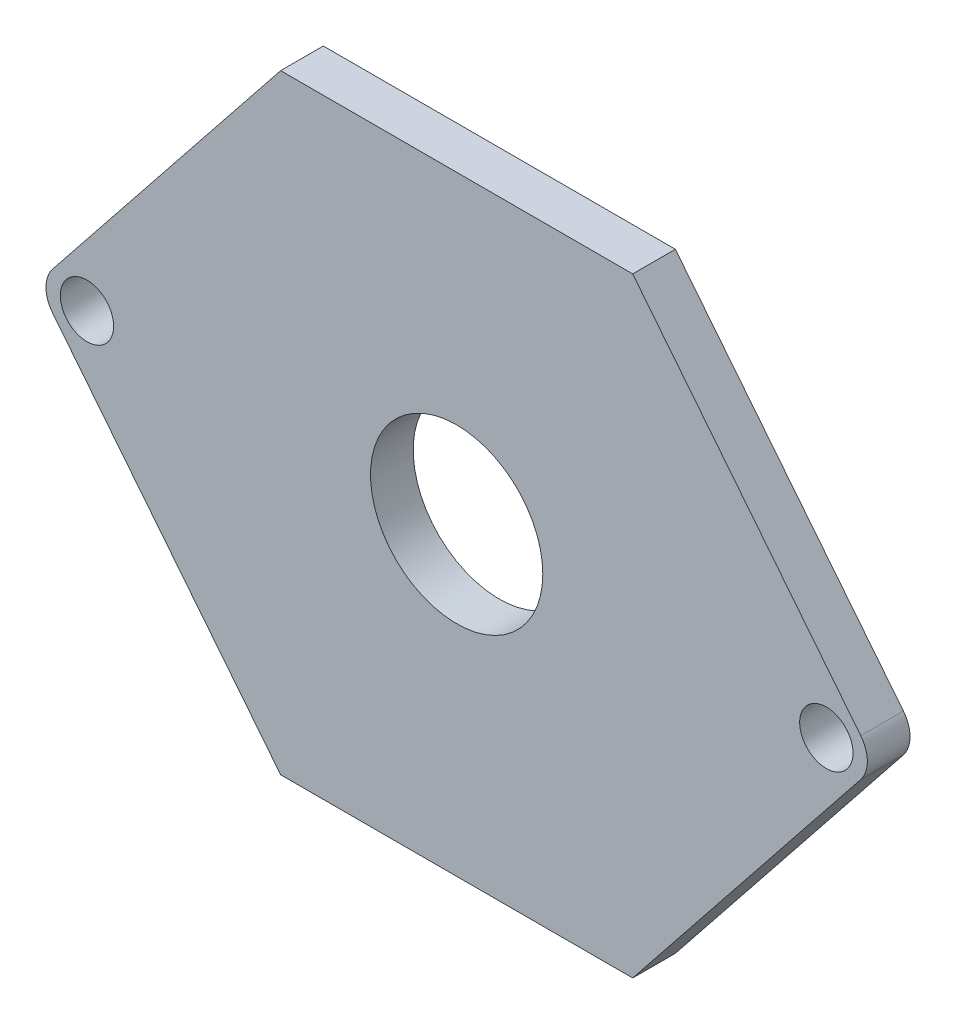
SolidWorks part; units mm, degrees
ref_plane "Front Plane" through (0, 0, 0) normal (0, 0, 1) x (1, 0, 0)
ref_plane "Top Plane" through (0, 0, 0) normal (0, 1, 0) x (1, 0, 0)
ref_plane "Right Plane" through (0, 0, 0) normal (1, 0, 0) x (0, 0, -1)
sketch "Sketch1" plane through (0, 0, 0) normal (0, 0, 1) x (1, 0, 0)
  line L0 (11.547, 20) -> (27.5, 0)
  line L1 (17.3205, 10) -> (11.547, 20) construction
  line L2 (11.547, 20) -> (-11.547, 20)
  line L3 (-11.547, 20) -> (-17.3205, 10) construction
  line L4 (-17.3205, -10) -> (-11.547, -20) construction
  line L5 (-11.547, -20) -> (11.547, -20)
  line L6 (11.547, -20) -> (17.3205, -10) construction
  line L7 (27.5, 0) -> (11.547, -20)
  line L8 (-11.547, 20) -> (-27.5, 0)
  line L9 (-27.5, 0) -> (-11.547, -20)
  line L10 (-17.3205, 10) -> (-23.094, 0) construction
  line L11 (-23.094, 0) -> (-17.3205, -10) construction
  line L12 (17.3205, -10) -> (23.094, 0) construction
  line L13 (23.094, 0) -> (17.3205, 10) construction
  line L14 (-24.25, 0) -> (24.25, 0) construction
  circle A0 centre (0, 0) radius 5.6507
  circle A1 centre (0, 0) radius 20 construction
  circle A2 centre (-24.25, 0) radius 1.75
  circle A3 centre (24.25, 0) radius 1.75
  point P15 (22.5, 0)
  point P22 (-22.5, 0)
  dimension "D1" = 40
  dimension "D3" = 3.5
  dimension "D2" = 55
  dimension "D4" = 45
extrude "Boss-Extrude1" add sketch "Sketch1" along normal blind 2.8
fillet "Fillet1" radius 2 2 edges at (27.5, 0, 1.4) (-27.5, 0, 1.4)
